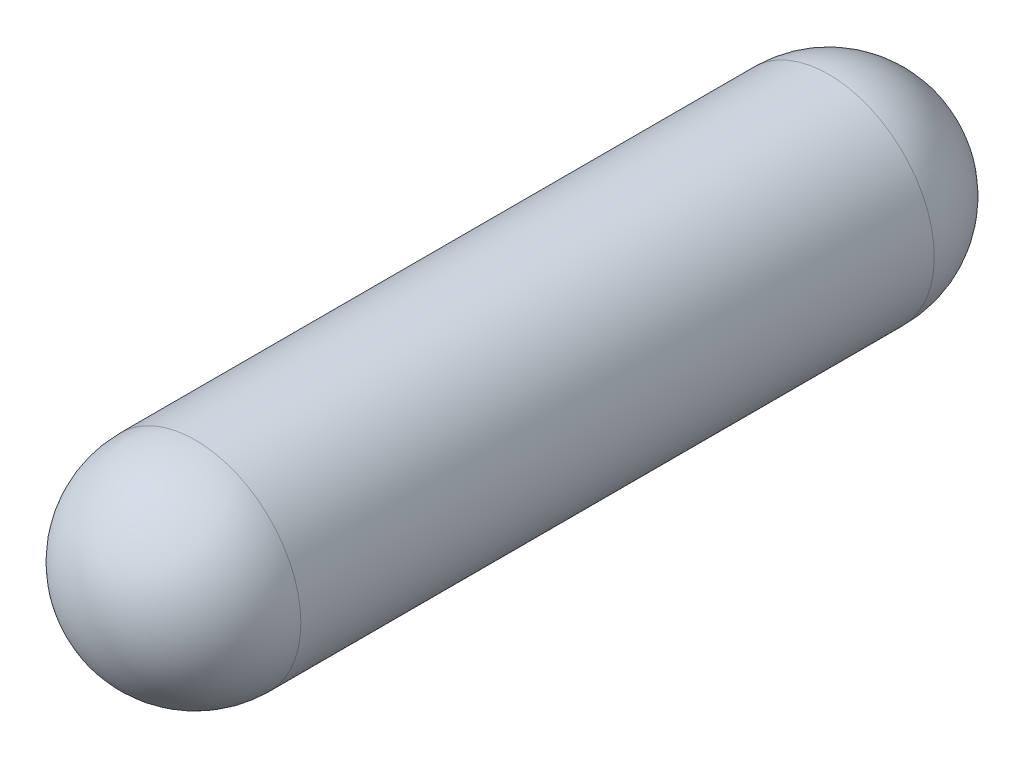
SolidWorks part; units mm, degrees
material "AISI 316 Annealed Stainless Steel Bar (SS)"
ref_plane "Front Plane" through (0, 0, 0) normal (0, 0, 1) x (1, 0, 0)
ref_plane "Top Plane" through (0, 0, 0) normal (0, 1, 0) x (1, 0, 0)
ref_plane "Right Plane" through (0, 0, 0) normal (1, 0, 0) x (0, 0, -1)
sketch "Sketch1" plane through (0, 0, 0) normal (0, 0, 1) x (1, 0, 0)
  circle A0 centre (0, 0) radius 1
  dimension "D1" = 2
extrude "Boss-Extrude1" add sketch "Sketch1" along normal blind 8
fillet "Fillet1" radius 1 2 edges at (1, 0, 0) (1, 0, 8)
